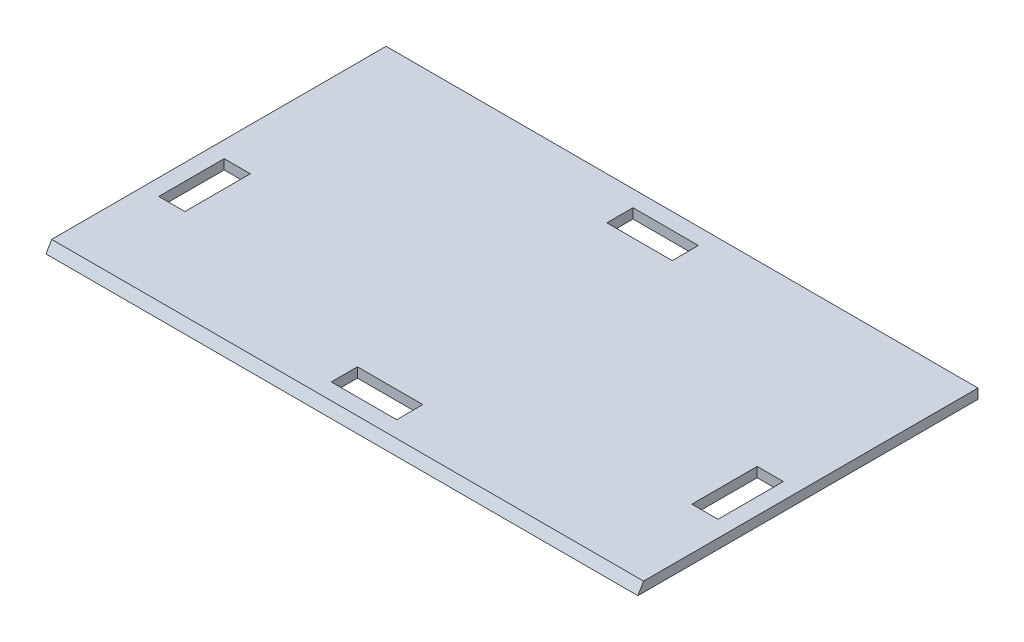
SolidWorks part; units mm, degrees
ref_plane "Alzado" through (0, 0, 0) normal (0, 0, 1) x (1, 0, 0)
ref_plane "Planta" through (0, 0, 0) normal (0, 1, 0) x (1, 0, 0)
ref_plane "Vista lateral" through (0, 0, 0) normal (1, 0, 0) x (0, 0, -1)
ref_plane "Plane1" through (-90.4992, 0, 0) normal (-1, 0, 0) x (0, 0, 1)
sketch "Sketch1" plane through (0, 0, 0) normal (1, 0, 0) x (0, 0, -1)
  line L0 (0.3513, 16.1816) -> (2.0833, 19.1816)
  line L1 (0.3513, 16.1816) -> (104.3513, 16.1816)
  line L4 (104.3513, 16.1816) -> (104.3513, 19.1816)
  line L5 (2.0833, 19.1816) -> (104.3513, 19.1816)
  line L6 (17.5014, 47.9678) -> (-0.6685, 16.4966) construction
  dimension "D1" = 104
  dimension "D2" = 3
extrude "Boss-Extrude1" add sketch "Sketch1" against normal blind 181
sketch "Sketch2" plane through (0, 19.1816, 0) normal (0, 1, 0) x (1, 0, 0)
  line L0 (-181, 104.3513) -> (0, 104.3513) construction
  line L1 (-100.4992, 99.3513) -> (-80.4992, 99.3513)
  line L2 (-100.4992, 99.3513) -> (-100.4992, 91.3513)
  line L3 (-100.4992, 91.3513) -> (-80.4992, 91.3513)
  line L4 (-80.4992, 99.3513) -> (-80.4992, 91.3513)
  line L5 (-90.4992, 24.1326) -> (-90.4992, -24.1326) construction
  line L6 (8.5008, -9.3287) -> (8.5008, 111.8513) construction
  line L7 (-4.9992, 49.8315) -> (-12.9992, 49.8315)
  line L8 (-4.9992, 49.8315) -> (-4.9992, 29.8315)
  line L9 (-4.9992, 29.8315) -> (-12.9992, 29.8315)
  line L10 (-12.9992, 49.8315) -> (-12.9992, 29.8315)
  line L11 (0, 39.8112) -> (-30.5018, 39.8112) construction
  line L12 (-181.9992, 3.3315) -> (1.0008, 3.3315) construction
  line L14 (0, 59.6707) -> (0, 20.0304) construction
  point P6 (-90.4992, 99.3513)
  dimension "D1" = 5
  dimension "D2" = 8
  dimension "D3" = 20
  dimension "D4" = 13.5
  dimension "D5" = 36.4796
  dimension "D6" = 8.5008
  dimension "D7" = 8.5008
  dimension "D8" = 26.5
  dimension "D9" = 8
  dimension "D10" = 20
extrude "Cut-Extrude1" cut sketch "Sketch2" against normal blind 4
mirror "Mirror1" about plane through (-90.4992, 0, 0) normal (-1, 0, 0) of "Cut-Extrude1"
ref_plane "Plane2" through (0, 0, -53.2163) normal (0, 0, -1) x (-1, 0, 0)
mirror "Mirror2" about plane through (0, 0, -53.2163) normal (0, 0, -1) of "Cut-Extrude1"
sketch "Sketch3" plane through (0, 19.1816, 0) normal (0, 1, 0) x (1, 0, 0)
  line L1 (-16.6835, 77.5617) -> (-4.9992, 77.5617)
  line L2 (-16.6835, 77.5617) -> (-16.6835, 55.607)
  line L3 (-16.6835, 55.607) -> (-4.9992, 55.607)
  line L4 (-4.9992, 77.5617) -> (-4.9992, 55.607)
  point P4 (-16.6835, 77.5617)
  point P5 (-16.6835, 55.607)
extrude "Boss-Extrude2" add sketch "Sketch3" against normal blind 3
